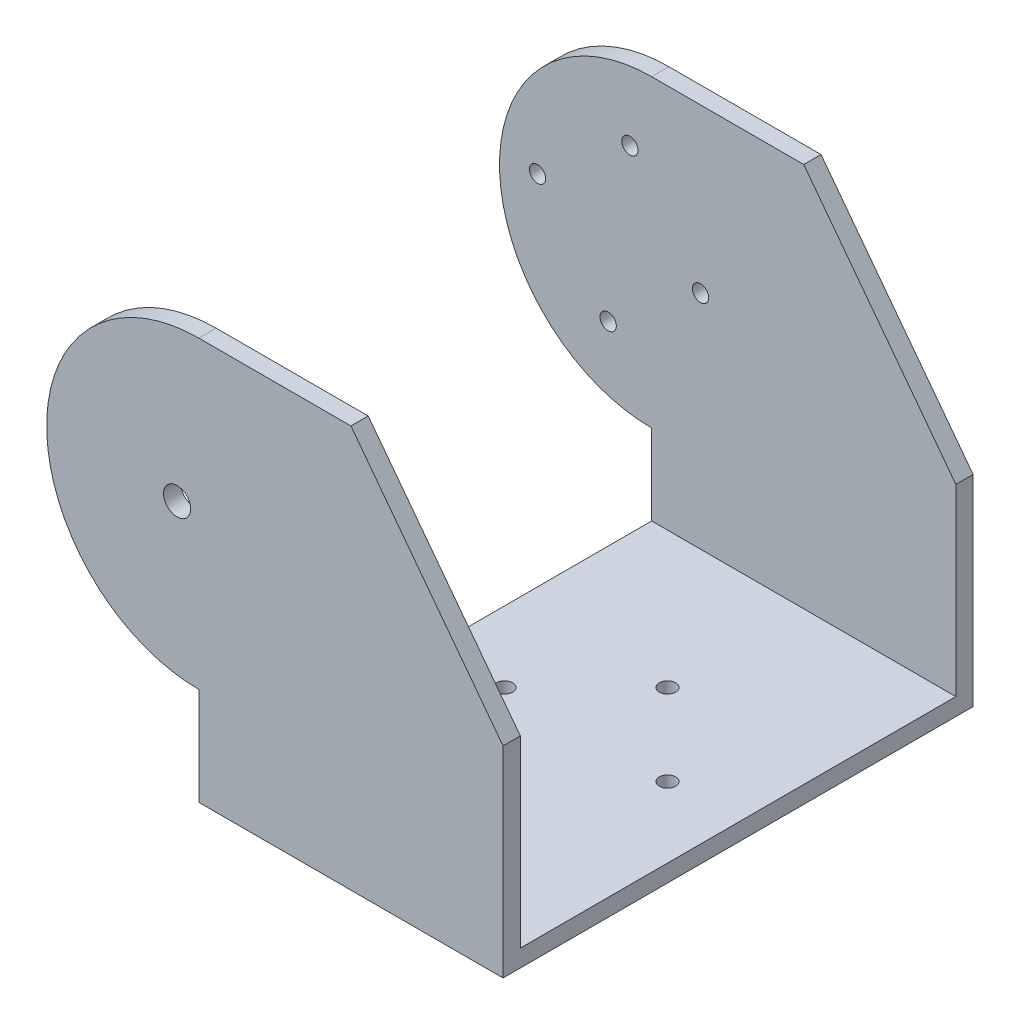
SolidWorks part; units mm, degrees
material "6061 Alloy"
ref_plane "Front Plane" through (0, 0, 0) normal (0, 0, 1) x (1, 0, 0)
ref_plane "Top Plane" through (0, 0, 0) normal (0, 1, 0) x (1, 0, 0)
ref_plane "Right Plane" through (0, 0, 0) normal (1, 0, 0) x (0, 0, -1)
sketch "Sketch1" plane through (0, 0, 0) normal (0, 1, 0) x (1, 0, 0)
  line L0 (-10.3213, 0) -> (10.2545, 0) construction
  line L1 (-14, 21.632) -> (14, 21.632)
  line L2 (-14, 21.632) -> (-14, -21.632)
  line L3 (-14, -21.632) -> (14, -21.632)
  line L4 (14, 21.632) -> (14, -21.632)
  line L5 (-14, 21.632) -> (14, -21.632) construction
  line L6 (-14, -21.632) -> (14, 21.632) construction
  line L7 (0, 8.8203) -> (0, -9.4436) construction
  circle A0 centre (0, 0) radius 12 construction
  circle A1 centre (0, 7.5) radius 0.75
  circle A2 centre (0, -7.5) radius 0.75
  circle A3 centre (7.5, 0) radius 0.75
  circle A4 centre (-7.5, 0) radius 0.75
  point P0 (0, 0)
  dimension "D1" = 24
  dimension "D6" = 1.5
  dimension "D2" = 7.5
  dimension "D3" = 15
  dimension "D4" = 7.5
  dimension "D5" = 15
  dimension "D7" = 43.264
  dimension "D8" = 28
extrude "Boss-Extrude1" add sketch "Sketch1" along normal blind 1.59
sketch "Sketch2" plane through (0, 1.59, 0) normal (0, 1, 0) x (1, 0, 0)
  line L0 (14, -21.632) -> (14, 21.632) construction
  line L1 (-14, 21.632) -> (14, 21.632)
  line L2 (-14, 21.632) -> (-14, 20.042)
  line L3 (-14, 20.042) -> (14, 20.042)
  line L4 (14, 21.632) -> (14, 20.042)
  line L6 (-14, -21.632) -> (14, -21.632)
  line L7 (-14, -21.632) -> (-14, -20.042)
  line L8 (-14, -20.042) -> (14, -20.042)
  line L9 (14, -21.632) -> (14, -20.042)
  dimension "D1" = 1.59
  dimension "D2" = 1.59
extrude "Boss-Extrude2" add sketch "Sketch2" along normal blind 35.41
sketch "Sketch7" plane through (0, 0, -21.632) normal (0, 0, -1) x (-1, 0, 0)
  line L0 (14, 37) -> (14, 0) construction
  line L1 (-14, 37) -> (14, 37) construction
  line L2 (14, 37) -> (14, 9)
  arc A0 (14, 9) -> (14, 37) centre (14, 23) ccw
  dimension "D1" = 28
extrude "Boss-Extrude5" add sketch "Sketch7" against normal up to surface (1.59 mm away) up to face at (0, 19.295, -20.042)
sketch "Sketch8" plane through (0, 0, 21.632) normal (0, 0, 1) x (1, 0, 0)
  line L0 (-14, 37) -> (-14, 0) construction
  line L1 (-14, 37) -> (14, 37) construction
  line L2 (-14, 37) -> (-14, 9)
  arc A0 (-14, 37) -> (-14, 9) centre (-14, 23) ccw
  dimension "D1" = 28
extrude "Boss-Extrude6" add sketch "Sketch8" against normal up to surface (1.59 mm away) up to face at (0, 19.295, 20.042)
sketch "Sketch9" plane through (0, 0, -21.632) normal (0, 0, -1) x (-1, 0, 0)
  line L0 (-14, 0) -> (14, 0) construction
  line L1 (-14, 37) -> (-14, 0) construction
  circle A0 centre (16, 23) radius 7.5 construction
  circle A1 centre (16, 30.5) radius 0.75
  circle A2 centre (24.5, 24) radius 0.75
  circle A3 centre (18, 15.5) radius 0.75
  circle A4 centre (9.5, 22) radius 0.75
  point P17 (17, 23)
  dimension "D3" = 15
  dimension "D4" = 1.5
  dimension "D1" = 23
  dimension "D2" = 30
  dimension "D5" = 4
extrude "Cut-Extrude3" cut sketch "Sketch9" against normal blind 10
sketch "Sketch10" plane through (0, 0, 21.632) normal (0, 0, 1) x (1, 0, 0)
  line L0 (-14, 0) -> (14, 0) construction
  line L2 (14, 37) -> (14, 0) construction
  circle A0 centre (-16, 23) radius 1.25
  dimension "D3" = 2.5
  dimension "D1" = 23
  dimension "D2" = 30
extrude "Cut-Extrude4" cut sketch "Sketch10" against normal blind 10
sketch "Sketch11" plane through (0, 0, 21.632) normal (0, 0, 1) x (1, 0, 0)
  line L0 (0, 37) -> (14, 18.5)
  line L1 (-14, 37) -> (14, 37) construction
  line L2 (14, 37) -> (14, 0) construction
  line L3 (14, 18.5) -> (14, 37)
  line L4 (14, 37) -> (0, 37)
extrude "Cut-Extrude5" cut sketch "Sketch11" against normal up to surface (43.264 mm away) up to face at (-25.25, 24, -21.632)
